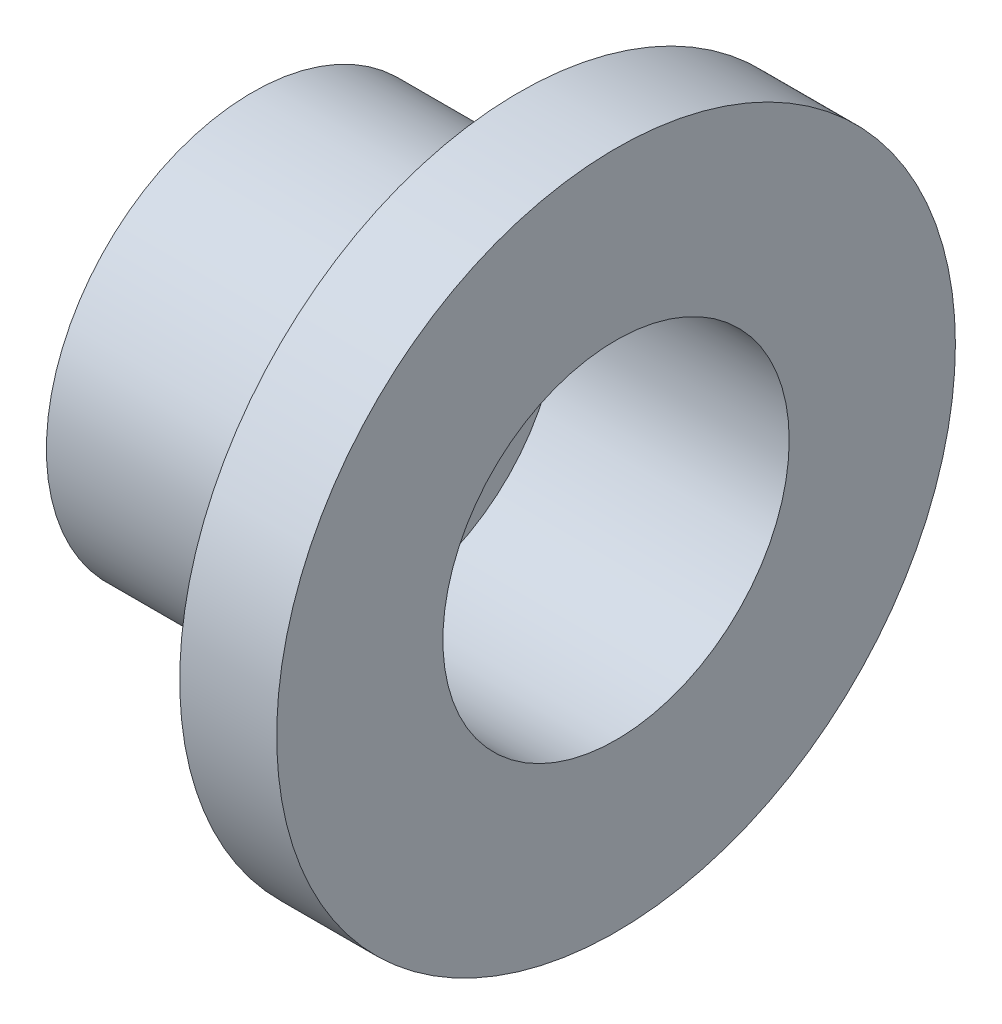
SolidWorks part; units mm, degrees
ref_plane "Front" through (0, 0, 0) normal (0, 0, 1) x (1, 0, 0)
ref_plane "Top" through (0, 0, 0) normal (0, 1, 0) x (1, 0, 0)
ref_plane "Right" through (0, 0, 0) normal (1, 0, 0) x (0, 0, -1)
sketch "Sketch1" plane through (0, 0, 0) normal (0, 0, 1) x (1, 0, 0)
  line L0 (0, 0) -> (0, 8.5)
  line L1 (0, 8.5) -> (11, 8.5)
  line L2 (11, 8.5) -> (11, 14)
  line L3 (11, 14) -> (15, 14)
  line L4 (15, 14) -> (15, 0)
  line L5 (15, 0) -> (0, 0)
  line L6 (0, 0) -> (-10.0109, 0) construction
  dimension "D1" = 17
  dimension "D2" = 11
  dimension "D3" = 4
  dimension "D4" = 28
revolve "Revolve1" add sketch "Sketch1" angle 360 about L6
hole_wizard "CBORE for 1/4 Binding Head Machine Screw1" positions "Sketch2" profile "Sketch4" counterbore size "1/4" standard "ANSI Inch"
sketch "Sketch2" plane through (15, 0, 0) normal (1, 0, 0) x (0, 0, -1)
  point P0 (0, 0)
sketch "Sketch4" plane through (15, 0, 0) normal (0, 1, 0) x (0, 0, -1)
  line L0 (0, 0) -> (0, 304.9611)
  line L1 (0, 304.9611) -> (3.2639, 303)
  line L2 (3.2639, 303) -> (3.2639, 9.525)
  line L3 (3.2639, 9.525) -> (7.1437, 9.525)
  line L4 (7.1437, 9.525) -> (7.1437, 0)
  line L5 (7.1437, 0) -> (0, 0)
  line L10 (0, 304.9611) -> (-3.2639, 303) construction
  line L11 (0, -6.35) -> (0, 107.95) construction
  dimension "Hole Dia." = 6.5278
  dimension "Hole Depth" = 303
  dimension "C'Bore Dia." = 14.2875
  dimension "C'Bore Depth" = 9.525
  dimension "Drill Angle" = 118
